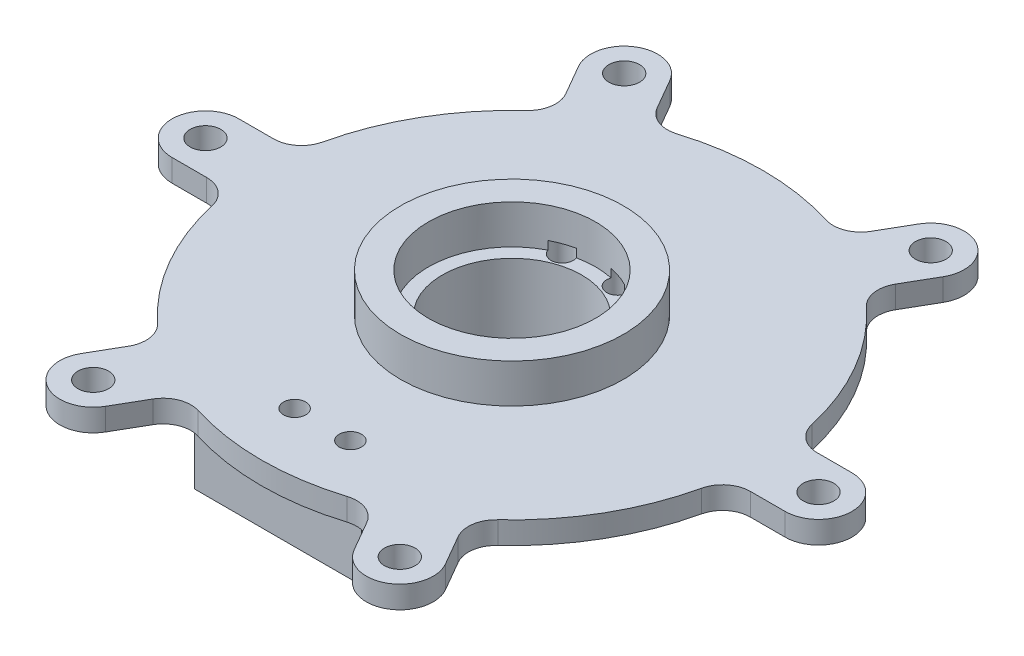
SolidWorks part; units mm, degrees
ref_plane "Спереди" through (0, 0, 0) normal (0, 0, 1) x (1, 0, 0)
ref_plane "Сверху" through (0, 0, 0) normal (0, 1, 0) x (1, 0, 0)
ref_plane "Справа" through (0, 0, 0) normal (1, 0, 0) x (0, 0, -1)
sketch "Эскиз1" plane through (0, 0, 0) normal (0, 1, 0) x (1, 0, 0)
  circle A0 centre (0, 0) radius 20
  circle A1 centre (0, 0) radius 15
  dimension "D1" = 40
  dimension "D2" = 30
extrude "Бобышка-Вытянуть1" add sketch "Эскиз1" along normal blind 7
sketch "Эскиз2" plane through (0, 0, 0) normal (0, -1, 0) x (1, 0, 0)
  circle A0 centre (0, 0) radius 70
  circle A1 centre (0, 0) radius 12.5
  dimension "D1" = 140
  dimension "D2" = 25
extrude "Бобышка-Вытянуть2" add sketch "Эскиз2" along normal blind 4
sketch "Эскиз3" plane through (0, -4, 0) normal (0, -1, 0) x (1, 0, 0)
  line L0 (10, -6.7) -> (10, 26.7) construction
  line L1 (15, -22) -> (-15, -22)
  line L2 (15, -22) -> (15, 42)
  line L3 (15, 42) -> (-15, 42)
  line L4 (-15, -22) -> (-15, 42)
  line L5 (-10, 26.7) -> (-10, -6.7) construction
  line L6 (-3.6083, -17) -> (3.6083, -17) construction
  line L7 (3.6083, 37) -> (-3.6083, 37) construction
  circle A0 centre (-5, 34) radius 2
  circle A1 centre (5, 34) radius 2
  circle A2 centre (-5, -14) radius 2
  circle A3 centre (5, -14) radius 2
  circle A4 centre (0, 0) radius 12.5
  dimension "D5" = 25
  dimension "D6" = 4
  dimension "D7" = 4
  dimension "D8" = 4
  dimension "D9" = 4
  dimension "D1" = 5
  dimension "D2" = 5
  dimension "D3" = 5
  dimension "D4" = 5
extrude "Бобышка-Вытянуть3" add sketch "Эскиз3" along normal blind 9.5
sketch "Эскиз4" plane through (0, 0, 0) normal (0, 1, 0) x (1, 0, 0)
  line L0 (-1000, 0) -> (49000, 0) construction
  circle A1 centre (0, 0) radius 80
  circle A2 centre (0, 0) radius 45
  dimension "D1" = 90
  dimension "D4" = 160
extrude "Вырез-Вытянуть1" cut sketch "Эскиз4" against normal blind 9.5
sketch "Эскиз6" plane through (0, -13.5, 0) normal (0, -1, 0) x (1, 0, 0)
  circle A0 centre (-5, 34) radius 2
  circle A1 centre (5, 34) radius 2
  circle A2 centre (-5, -14) radius 2
  circle A3 centre (5, -14) radius 2
extrude "Вырез-Вытянуть2" cut sketch "Эскиз6" against normal blind 15
sketch "Эскиз7" plane through (0, 0, 0) normal (0, 1, 0) x (1, 0, 0)
  line L0 (0, 0) -> (-55, 0) construction
  line L1 (-55, 6) -> (-40, 6)
  line L2 (-40, 6) -> (-40, -6)
  line L3 (-40, -6) -> (-55, -6)
  circle A7 centre (-55, 0) radius 2.75
  circle A9 centre (0, 0) radius 45 construction
  arc A10 (-55, 6) -> (-55, -6) centre (-55, 0) ccw
  dimension "D1" = 5.5
  dimension "D3" = 12
  dimension "D2" = 55
  dimension "D4" = 15
extrude "Бобышка-Вытянуть4" add sketch "Эскиз7" against normal blind 4
pattern_circular "Круговой массив1" count 6 over 360 about axis through (0, 0, 0) along (0, 1, 0) of "Бобышка-Вытянуть4"
fillet "Скругление2" radius 5 12 edges at (-44.5982, -2, 6) (-27.4953, -2, 35.6232) (-17.103, -2, 41.6232) (17.103, -2, 41.6232) (27.4953, -2, 35.6232) (44.5982, -2, 6) (44.5982, -2, -6) (27.4953, -2, -35.6232) (17.103, -2, -41.6232) (-17.103, -2, -41.6232) (-27.4953, -2, -35.6232) (-44.5982, -2, -6)
